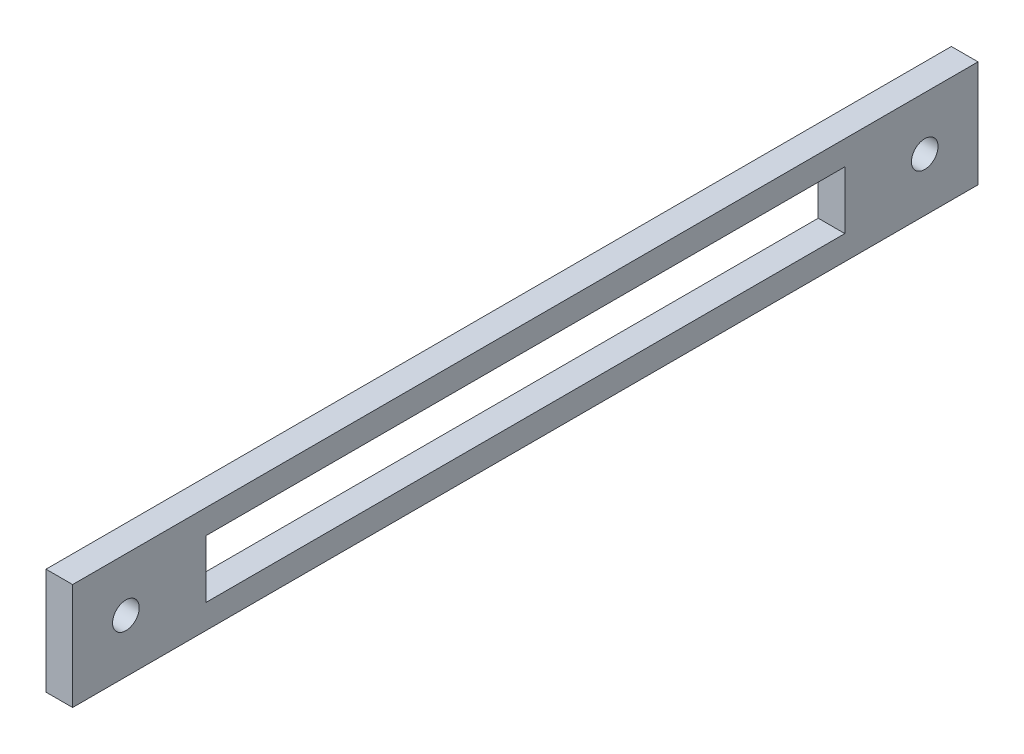
SolidWorks part; units mm, degrees
ref_plane "前视基准面" through (0, 0, 0) normal (0, 0, 1) x (1, 0, 0)
ref_plane "上视基准面" through (0, 0, 0) normal (0, 1, 0) x (1, 0, 0)
ref_plane "右视基准面" through (0, 0, 0) normal (1, 0, 0) x (0, 0, -1)
other "Configuration Table"
sketch "草图1" plane through (0, 0, 0) normal (1, 0, 0) x (0, 0, -1)
  line L0 (-150, 0) -> (150, 0) construction
  line L1 (-170, 20) -> (170, 20)
  line L2 (-170, 20) -> (-170, -20)
  line L3 (-170, -20) -> (170, -20)
  line L4 (170, 20) -> (170, -20)
  line L8 (-120, 10.8586) -> (120, 10.8586)
  line L9 (-120, 10.8586) -> (-120, -10.8586)
  line L10 (-120, -10.8586) -> (120, -10.8586)
  line L11 (120, 10.8586) -> (120, -10.8586)
  line L12 (-120, 10.8586) -> (120, -10.8586) construction
  line L13 (-120, -10.8586) -> (120, 10.8586) construction
  circle A0 centre (-150, 0) radius 5
  circle A1 centre (150, 0) radius 5
  point P10 (0, 0)
  point P12 (-170, 0)
  dimension "D2" = 10
  dimension "D4" = 20
  dimension "D1" = 300
  dimension "D3" = 20
  dimension "D5" = 20
  dimension "D6" = 120
  dimension "D7" = 10.8586
extrude "凸台-拉伸1" add sketch "草图1" along normal blind 10 contours A1 L1 A0 L3 | A0 L2 L3 | A0 L1 L2 | A1 L4 L1 | A1 L3 L4
